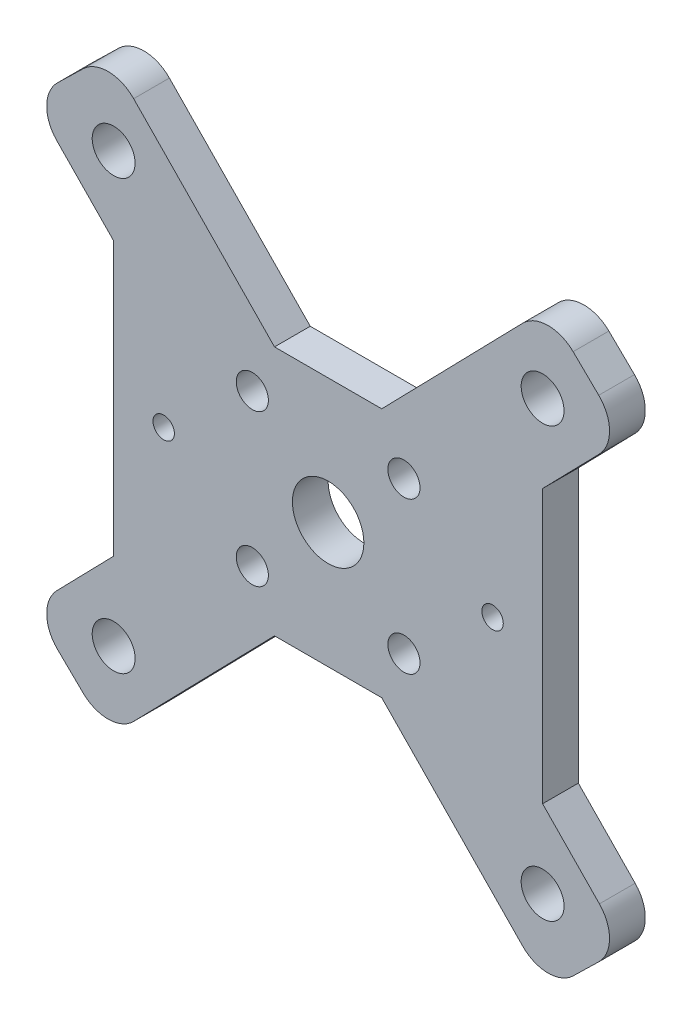
SolidWorks part; units mm, degrees
ref_plane "Plan de face" through (0, 0, 0) normal (0, 0, 1) x (1, 0, 0)
ref_plane "Plan de dessus" through (0, 0, 0) normal (0, 1, 0) x (1, 0, 0)
ref_plane "Plan de droite" through (0, 0, 0) normal (1, 0, 0) x (0, 0, -1)
sketch "Esquisse1" plane through (0, 0, 0) normal (0, 0, 1) x (1, 0, 0)
  line L0 (-10.605, 10.605) -> (-10.605, -10.605) construction
  line L1 (7.5, -17.5) -> (-7.5, -17.5)
  line L2 (17.5, -7.5) -> (17.5, 7.5)
  line L3 (7.5, 17.5) -> (-7.5, 17.5)
  line L4 (-17.5, -7.5) -> (-17.5, 7.5)
  line L5 (17.5, -17.5) -> (-17.5, 17.5) construction
  line L6 (17.5, 17.5) -> (-17.5, -17.5) construction
  line L7 (-10.605, 10.605) -> (10.605, 10.605) construction
  line L8 (10.605, 10.605) -> (10.605, -10.605) construction
  circle A0 centre (0, 0) radius 8
  circle A1 centre (-10.605, 10.605) radius 2.25
  circle A2 centre (10.605, 10.605) radius 2.25
  circle A3 centre (-10.605, -10.605) radius 2.25
  circle A4 centre (10.605, -10.605) radius 2.25
  arc A5 (-7.5, -17.5) -> (-17.5, -7.5) centre (-7.5, -7.5) cw
  arc A6 (7.5, -17.5) -> (17.5, -7.5) centre (7.5, -7.5) ccw
  arc A7 (17.5, 7.5) -> (7.5, 17.5) centre (7.5, 7.5) ccw
  arc A8 (-7.5, 17.5) -> (-17.5, 7.5) centre (-7.5, 7.5) ccw
  point P0 (0, 0)
  point P16 (0, 0)
  point P17 (8.9507, -11.9448)
  point P18 (10.605, 0)
  point P19 (0, 10.605)
  point P20 (-10.605, 0)
  point P21 (0, 0)
  point P22 (9.4172, 10.605)
  point P35 (0, 0)
  dimension "D1" = 4.5
  dimension "D2" = 4.5
  dimension "D3" = 4.5
  dimension "D4" = 4.5
  dimension "D7" = 16
  dimension "D10" = 10
  dimension "D5" = 21.21
  dimension "D6" = 21.21
  dimension "D8" = 35
  dimension "D9" = 35
extrude "Boss.-Extru.1" add sketch "Esquisse1" along normal blind 5
sketch "Esquisse2" plane through (0, 0, 5) normal (0, 0, 1) x (1, 0, 0)
  line L0 (-38.0784, 38.0784) -> (30.6138, -30.6138) construction
  line L1 (37.8813, 37.8813) -> (-34.8497, -34.8497) construction
  line L2 (-17.4124, 6.1793) -> (-37.9445, 27.2476)
  line L3 (-37.8534, 34.3181) -> (-34.2726, 37.8078)
  line L4 (-27.2021, 37.7167) -> (-7.5, 17.5)
  line L5 (-30, 30) -> (-42.1259, 42.1259) construction
  line L6 (0, 38.0784) -> (0, -34.8497) construction
  line L7 (-51.3686, 0) -> (60.5572, 0) construction
  line L8 (37.8534, 34.3181) -> (34.2726, 37.8078)
  line L9 (17.4124, 6.1793) -> (37.9445, 27.2476)
  line L10 (27.2021, 37.7167) -> (7.5, 17.5)
  line L11 (17.4124, -6.1793) -> (37.9445, -27.2476)
  line L12 (27.2021, -37.7167) -> (7.5, -17.5)
  line L13 (37.8534, -34.3181) -> (34.2726, -37.8078)
  line L14 (-37.8534, -34.3181) -> (-34.2726, -37.8078)
  line L15 (-17.4124, -6.1793) -> (-37.9445, -27.2476)
  line L16 (-27.2021, -37.7167) -> (-7.5, -17.5)
  circle A0 centre (-10.605, -10.605) radius 2.25 construction
  circle A1 centre (10.605, -10.605) radius 2.25 construction
  circle A2 centre (10.605, 10.605) radius 2.25 construction
  circle A3 centre (-10.605, 10.605) radius 2.25 construction
  circle A4 centre (-10.605, -10.605) radius 2.25
  circle A5 centre (10.605, -10.605) radius 2.25
  circle A6 centre (10.605, 10.605) radius 2.25
  circle A7 centre (-10.605, 10.605) radius 2.25
  circle A8 centre (-30, 30) radius 3
  circle A9 centre (30, 30) radius 3
  circle A10 centre (-30, -30) radius 3
  circle A11 centre (30, -30) radius 3
  arc A12 (-7.5, 17.5) -> (-17.5, 7.5) centre (-7.5, 7.5) ccw construction
  arc A13 (-7.5, 17.5) -> (-17.4124, 6.1793) centre (-7.5, 7.5) ccw
  arc A14 (7.5, 17.5) -> (17.4124, 6.1793) centre (7.5, 7.5) cw
  arc A15 (7.5, -17.5) -> (17.4124, -6.1793) centre (7.5, -7.5) ccw
  arc A16 (-7.5, -17.5) -> (-17.4124, -6.1793) centre (-7.5, -7.5) cw
  arc A17 (-37.8534, -34.3181) -> (-37.9445, -27.2476) centre (-34.3637, -30.7373) cw
  arc A18 (-34.2726, -37.8078) -> (-27.2021, -37.7167) centre (-30.7829, -34.227) ccw
  arc A19 (27.2021, -37.7167) -> (34.2726, -37.8078) centre (30.7829, -34.227) ccw
  arc A20 (37.9445, -27.2476) -> (37.8534, -34.3181) centre (34.3637, -30.7373) cw
  arc A21 (37.8534, 34.3181) -> (37.9445, 27.2476) centre (34.3637, 30.7373) cw
  arc A22 (34.2726, 37.8078) -> (27.2021, 37.7167) centre (30.7829, 34.227) ccw
  arc A23 (-34.2726, 37.8078) -> (-27.2021, 37.7167) centre (-30.7829, 34.227) cw
  arc A24 (-37.9445, 27.2476) -> (-37.8534, 34.3181) centre (-34.3637, 30.7373) cw
  point P30 (-36.063, 36.063)
  point P37 (-8.4349, 17.4562)
  point P39 (-41.192, 30.5918)
  point P40 (-6.7466, 17.4716)
  point P41 (0, 0)
  point P59 (-41.4342, -30.8285)
  point P62 (-30.6917, -41.2975)
  point P65 (30.6917, -41.2975)
  point P68 (41.4342, -30.8285)
  point P71 (41.4342, 30.8285)
  point P74 (30.6917, 41.2975)
  point P77 (-30.6917, 41.2975)
  point P80 (-41.4342, 30.8285)
  arc M26 (-17.5, -7.5) -> (-7.5, -17.5) centre (-7.5, -7.5) ccw
  arc M28 (7.5, -17.5) -> (17.5, -7.5) centre (7.5, -7.5) ccw
  line M29 (17.5, -7.5) -> (17.5, 7.5)
  arc M30 (17.5, 7.5) -> (7.5, 17.5) centre (7.5, 7.5) ccw
  arc M32 (-7.5, 17.5) -> (-17.5, 7.5) centre (-7.5, 7.5) ccw
  line M33 (-17.5, 7.5) -> (-17.5, -7.5)
  dimension "D2" = 6
  dimension "D5" = 5
  dimension "D1" = 30
  dimension "D3" = 15
  dimension "D4" = 36
extrude "Boss.-Extru.2" add sketch "Esquisse2" against normal blind 5 contours A24 L2 L4 A23 L3 A8 M33 M32 | L8 A22 L10 L9 A21 A9 M30 M29 | A20 L11 L12 A19 L13 A11 M29 M28 | L14 A18 L16 L15 A17 A10 M26 M33
sketch "Esquisse3" plane through (0, 0, 5) normal (0, 0, 1) x (1, 0, 0)
  line L0 (17.5, -6.2692) -> (37.9445, -27.2476) construction
  line L1 (17.5, -6.2692) -> (17.5, 6.2692) construction
  line L2 (17.5, 6.2692) -> (37.9445, 27.2476) construction
  line L3 (-17.5, -6.2692) -> (-37.9445, -27.2476) construction
  line L4 (-17.5, 6.2692) -> (-17.5, -6.2692) construction
  line L5 (-17.5, 6.2692) -> (-37.9445, 27.2476) construction
  line L6 (17.5, -6.2692) -> (37.9445, -27.2476)
  line L7 (17.5, -6.2692) -> (17.5, 6.2692)
  line L8 (17.5, 6.2692) -> (37.9445, 27.2476)
  line L9 (-17.5, -6.2692) -> (-37.9445, -27.2476)
  line L10 (-17.5, 6.2692) -> (-17.5, -6.2692)
  line L11 (-17.5, 6.2692) -> (-37.9445, 27.2476)
  line L12 (-30, 19.0956) -> (-30, -19.0956)
  line L13 (0, 24.6319) -> (0, -34.2142) construction
  line L14 (17.5, -6.2692) -> (37.9445, -27.2476)
  line L15 (17.5, 6.2692) -> (17.5, -6.2692)
  line L16 (17.5, 6.2692) -> (37.9445, 27.2476)
  line L17 (30, 19.0956) -> (30, -19.0956)
  circle A0 centre (-23, 0) radius 1.5
  circle A1 centre (23, 0) radius 1.5
  circle A2 centre (0, 0) radius 5
  circle A3 centre (0, 0) radius 8 construction
  circle A4 centre (0, 0) radius 8
  line M7 (-17.5, 6.2692) -> (-17.5, -6.2692)
  line M8 (-17.5, -6.2692) -> (-37.9445, -27.2476)
  line M19 (17.5, -6.2692) -> (17.5, 6.2692)
  line M20 (17.5, 6.2692) -> (37.9445, 27.2476)
  dimension "D2" = 3
  dimension "D4" = 10
  dimension "D1" = 30
  dimension "D3" = 23
extrude "Boss.-Extru.3" add sketch "Esquisse3" against normal blind 5 contours L11 L12 A0 M8 M7 | L17 L14 A1 M20 M19 | A4 | A2
